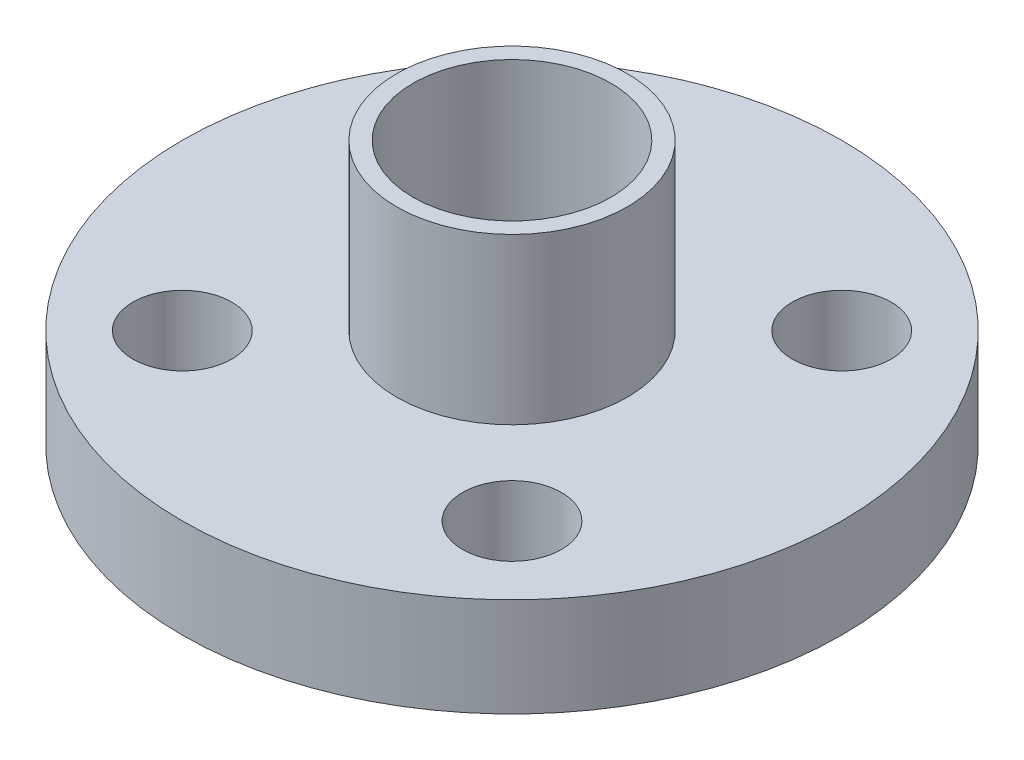
SolidWorks part; units mm, degrees
ref_plane "前视基准面" through (0, 0, 0) normal (0, 0, 1) x (1, 0, 0)
ref_plane "上视基准面" through (0, 0, 0) normal (0, 1, 0) x (1, 0, 0)
ref_plane "右视基准面" through (0, 0, 0) normal (1, 0, 0) x (0, 0, -1)
other "Configuration Table"
sketch "草图1" plane through (0, 0, 0) normal (0, 1, 0) x (1, 0, 0)
  line L1 (-5, -5) -> (5, -5)
  line L2 (-5, -5) -> (-5, 5)
  line L3 (-5, 5) -> (5, 5)
  line L4 (5, -5) -> (5, 5)
  line L5 (-5, -5) -> (5, 5) construction
  line L6 (-5, 5) -> (5, -5) construction
  circle A0 centre (0, 0) radius 10
  circle A1 centre (-5, 5) radius 1.5
  circle A2 centre (5, 5) radius 1.5
  circle A3 centre (5, -5) radius 1.5
  circle A4 centre (-5, -5) radius 1.5
  point P17 (0, 0)
  dimension "D1" = 20
  dimension "D4" = 3
  dimension "D2" = 10
  dimension "D3" = 10
  dimension "D5" = 4
extrude "凸台-拉伸1" add sketch "草图1" along normal blind 3 contours A4 L1 A3 L4 A2 L3 A1 L2 | A0 A4 L2 A1 L3 A2 L4 A3 L1
sketch "草图2" plane through (0, 3, 0) normal (0, 1, 0) x (1, 0, 0)
  circle A0 centre (0, 0) radius 3
  circle A1 centre (0, 0) radius 3.5
  dimension "D1" = 6
  dimension "D2" = 7
extrude "凸台-拉伸2" add sketch "草图2" along normal blind 5
sketch "草图3" plane through (0, 3, 0) normal (0, 1, 0) x (1, 0, 0)
  circle A0 centre (0, 0) radius 1.5
  dimension "D1" = 3
extrude "切除-拉伸1" cut sketch "草图3" against normal blind 5
